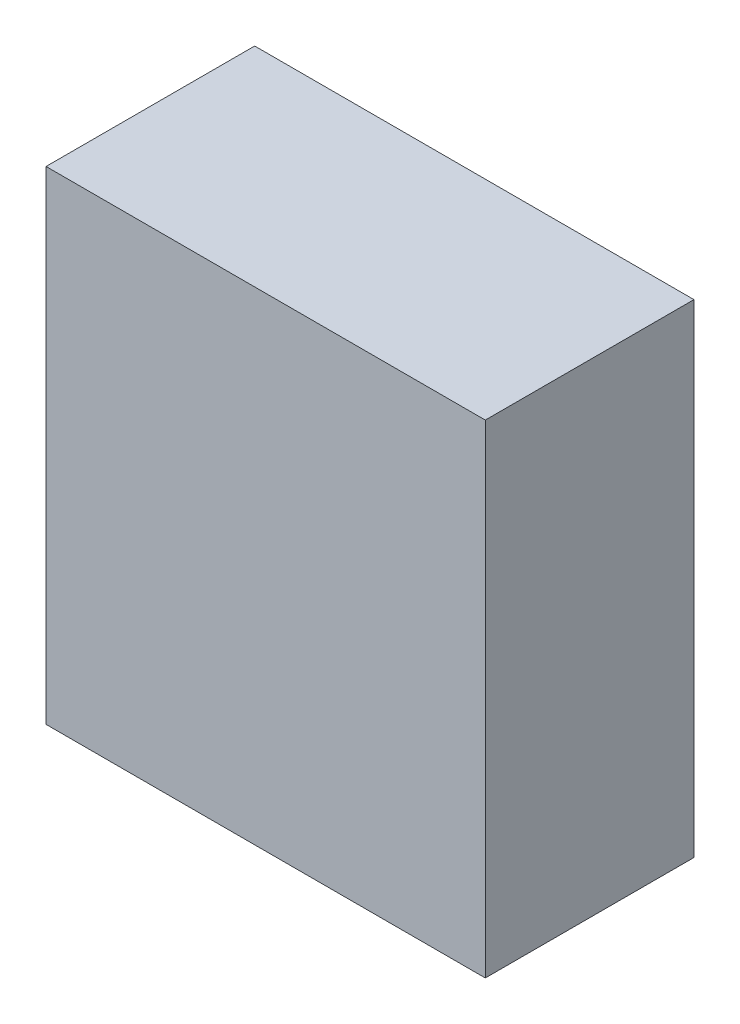
SolidWorks part; units mm, degrees
ref_plane "Спереди" through (0, 0, 0) normal (0, 0, 1) x (1, 0, 0)
ref_plane "Сверху" through (0, 0, 0) normal (0, 1, 0) x (1, 0, 0)
ref_plane "Справа" through (0, 0, 0) normal (1, 0, 0) x (0, 0, -1)
sketch "Эскиз1" plane through (0, 0, 0) normal (0, 0, 1) x (1, 0, 0)
  line L1 (-400, 440) -> (400, 440)
  line L2 (-400, 440) -> (-400, -440)
  line L3 (-400, -440) -> (400, -440)
  line L4 (400, 440) -> (400, -440)
  line L5 (-400, 440) -> (400, -440) construction
  line L6 (-400, -440) -> (400, 440) construction
  point P0 (0, 0)
extrude "Бобышка-Вытянуть1" add sketch "Эскиз1" along normal blind 380 contours L2 L1 L4 L3
sketch "Эскиз2" plane through (0, 0, 380) normal (0, 0, 1) x (1, 0, 0)
  line L0 (0, 440) -> (0, -440)
  line L1 (-400, 440) -> (400, 440) construction
  line L2 (-400, -440) -> (400, -440) construction
  line L3 (-400, 0) -> (0, 0)
  line L4 (-400, 440) -> (-400, -440) construction
  line L5 (-400, 241.4673) -> (0, 241.4673)
  circle A0 centre (-196.287, 338.2573) radius 17.6701
  circle A1 centre (-202.6906, 118.131) radius 17.6701
  circle A2 centre (-65.4226, -98.1348) radius 17.6701
  circle A3 centre (62.375, 28.7602) radius 17.6701
